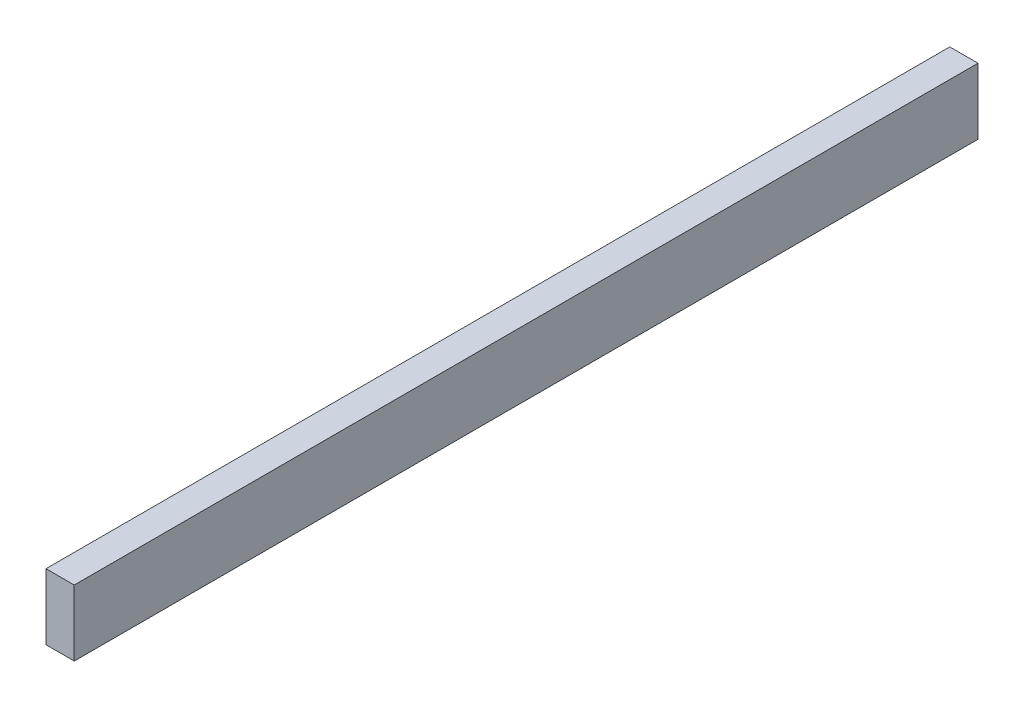
SolidWorks part; units mm, degrees
ref_plane "Front Plane" through (0, 0, 0) normal (0, 0, 1) x (1, 0, 0)
ref_plane "Top Plane" through (0, 0, 0) normal (0, 1, 0) x (1, 0, 0)
ref_plane "Right Plane" through (0, 0, 0) normal (1, 0, 0) x (0, 0, -1)
sketch "Sketch1" plane through (0, 0, 0) normal (1, 0, 0) x (0, 0, -1)
  line L1 (0, 0) -> (609.6, 0)
  line L2 (0, 0) -> (0, 44.45)
  line L3 (0, 44.45) -> (609.6, 44.45)
  line L4 (609.6, 0) -> (609.6, 44.45)
  dimension "D1" = 609.6
  dimension "D2" = 44.45
extrude "Boss-Extrude1" add sketch "Sketch1" along normal blind 19.05
